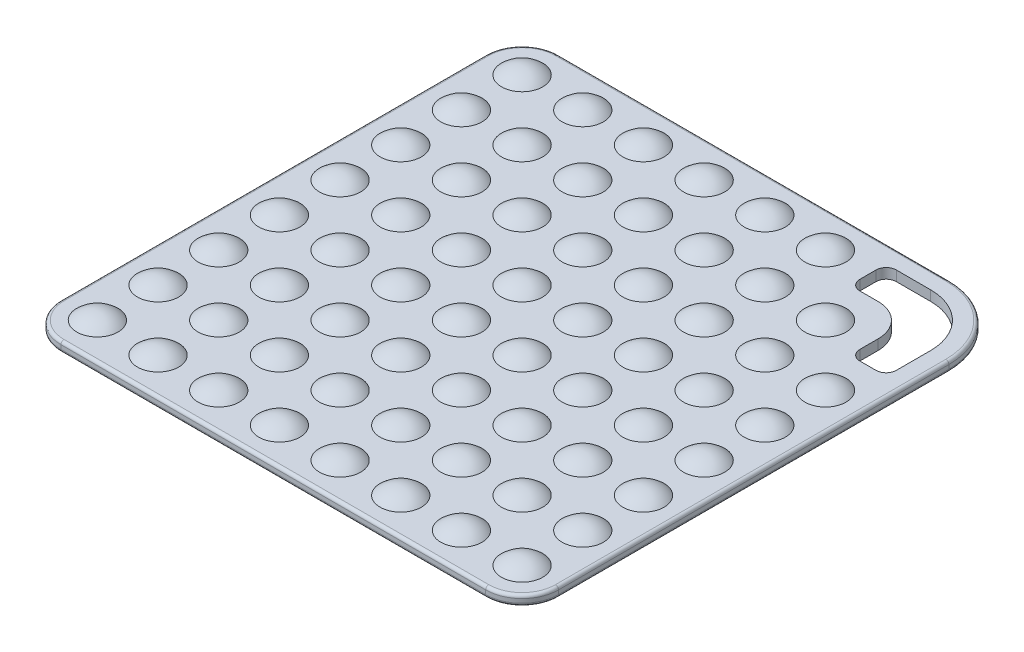
SolidWorks part; units mm, degrees
ref_plane "Front Plane" through (0, 0, 0) normal (0, 0, 1) x (1, 0, 0)
ref_plane "Top Plane" through (0, 0, 0) normal (0, 1, 0) x (1, 0, 0)
ref_plane "Right Plane" through (0, 0, 0) normal (1, 0, 0) x (0, 0, -1)
sketch "Sketch1" plane through (0, 0, 0) normal (0, 1, 0) x (1, 0, 0)
  line L1 (-105, 123) -> (88, 123)
  line L2 (-123, 105) -> (-123, -105)
  line L3 (-105, -123) -> (105, -123)
  line L4 (123, 88) -> (123, -105)
  arc A0 (-105, -123) -> (-123, -105) centre (-105, -105) cw
  arc A1 (-105, 123) -> (-123, 105) centre (-105, 105) ccw
  arc A2 (123, -105) -> (105, -123) centre (105, -105) cw
  arc A3 (123, 88) -> (88, 123) centre (88, 88) ccw
  dimension "D5" = 18
  dimension "D6" = 18
  dimension "D7" = 18
  dimension "D8" = 35
  dimension "D1" = 246
  dimension "D2" = 246
  dimension "D3" = 123
  dimension "D4" = 123
extrude "Boss-Extrude1" add sketch "Sketch1" along normal blind 5
fillet "Fillet1" radius 1.5 8 edges at (-123, 5, 0) (-117.7279, 5, -117.7279) (-8.5, 5, -123) (112.7487, 5, -112.7487) (123, 5, 8.5) (117.7279, 5, 117.7279) (0, 5, 123) (-117.7279, 5, 117.7279)
fillet "Fillet2" radius 1.5 8 edges at (-117.7279, 0, 117.7279) (-123, 0, 0) (-117.7279, 0, -117.7279) (-8.5, 0, -123) (112.7487, 0, -112.7487) (123, 0, 8.5) (117.7279, 0, 117.7279) (0, 0, 123)
sketch "Sketch2" plane through (0, 5, 0) normal (0, 1, 0) x (1, 0, 0)
  line L0 (105, -121.5) -> (105, -102.9916) construction
  line L2 (105, -123) -> (105, -121.5) construction
  point P3 (105, -122.25)
ref_plane "Plane1" through (105, 0, 0) normal (1, 0, 0) x (0, 0, -1)
sketch "Sketch4" plane through (105, 0, 0) normal (1, 0, 0) x (0, 0, -1)
  line L0 (-105, 5) -> (-105, 10.5422) construction
  line L2 (-105, 3.5) -> (-105, 1.5) construction
  line L3 (-200121.5, 5) -> (199897.0084, 5) construction
  line L4 (-105, 9) -> (-105, 5)
  line L5 (-105, 5) -> (-115.198, 5)
  arc A0 (-115.198, 5) -> (-105, 9) centre (-105, -6) cw
  point P3 (-105, 2.5)
  point P8 (0, 0)
  dimension "D1" = 15
  dimension "D2" = 4
revolve "Revolve1" add sketch "Sketch4" angle 360 about L0
sketch "Sketch5" plane through (0, 5, 0) normal (0, 1, 0) x (1, 0, 0)
  line L0 (121.5, -105) -> (-208.782, -105) construction
pattern_linear "LPattern4" count 8 spacing 30 along (0, 0, -1) count 8 spacing 30 along (-1, 0, 0) skipping (6, 0), (7, 0), (7, 1) of "Revolve1"
sketch "Sketch7" plane through (0, 5, 0) normal (0, 1, 0) x (1, 0, 0)
  line L0 (66, 109) -> (66, 101)
  line L1 (71, 96) -> (80, 96)
  line L2 (71, 114) -> (88, 114)
  line L3 (114, 88) -> (114, 71)
  line L4 (109, 66) -> (101, 66)
  line L5 (96, 71) -> (96, 80)
  arc A0 (88, 114) -> (114, 88) centre (88, 88) cw
  arc A1 (80, 96) -> (96, 80) centre (80, 80) cw
  arc A2 (123, 88) -> (88, 123) centre (88, 88) ccw construction
  arc A3 (66, 109) -> (71, 114) centre (71, 109) cw
  arc A4 (66, 101) -> (71, 96) centre (71, 101) ccw
  arc A5 (101, 66) -> (96, 71) centre (101, 71) cw
  arc A6 (114, 71) -> (109, 66) centre (109, 71) cw
  point P10 (83.2598, 100.8752)
  point P20 (96, 66)
  point P23 (114, 66)
  dimension "D1" = 16
  dimension "D2" = 26
  dimension "D3" = 18
  dimension "D7" = 5
  dimension "D8" = 5
  dimension "D9" = 5
  dimension "D10" = 5
  dimension "D4" = 18
  dimension "D5" = 22
  dimension "D6" = 22
extrude "Cut-Extrude1" cut sketch "Sketch7" against normal blind 5
